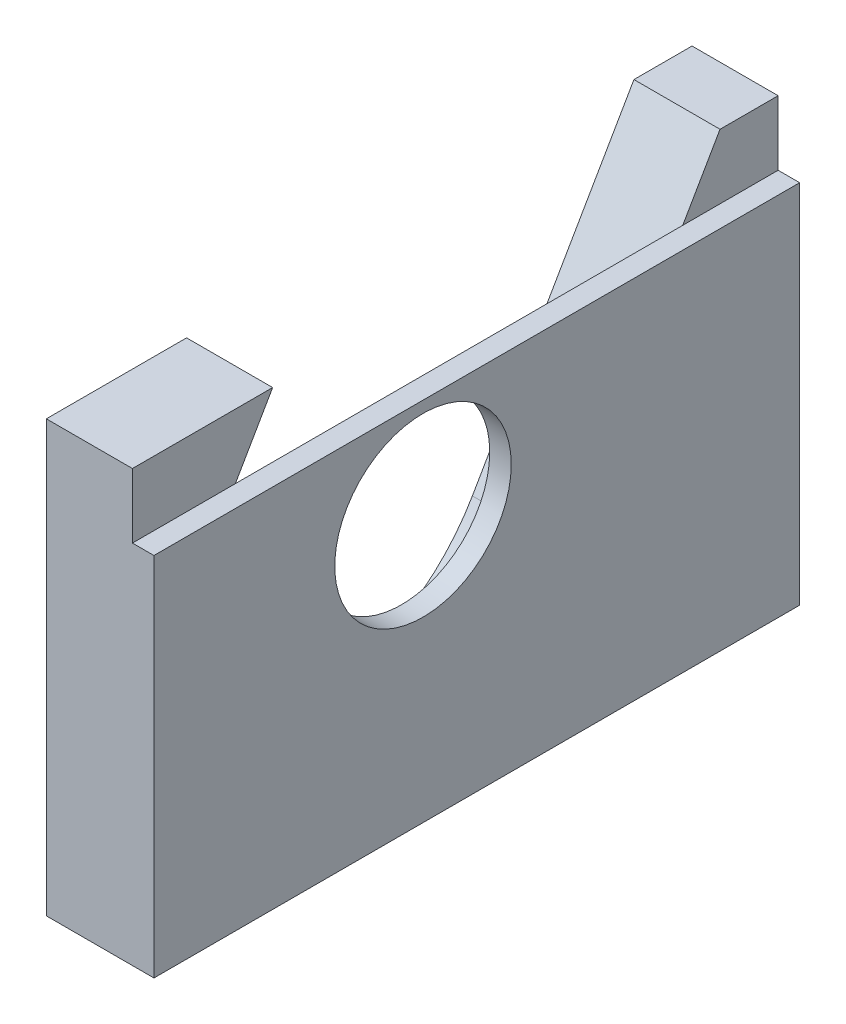
SolidWorks part; units mm, degrees
ref_plane "Front Plane" through (0, 0, 0) normal (0, 0, 1) x (1, 0, 0)
ref_plane "Top Plane" through (0, 0, 0) normal (0, 1, 0) x (1, 0, 0)
ref_plane "Right Plane" through (0, 0, 0) normal (1, 0, 0) x (0, 0, -1)
sketch "Sketch1" plane through (0, 0, 0) normal (1, 0, 0) x (0, 0, -1)
  line L1 (0, 0) -> (30, 0)
  line L2 (0, 0) -> (0, 20)
  line L3 (0, 20) -> (30, 20)
  line L4 (30, 0) -> (30, 20)
  dimension "D1" = 30
  dimension "D2" = 20
extrude "Boss-Extrude1" add sketch "Sketch1" along normal blind 4
sketch "Sketch2" plane through (4, 0, 0) normal (1, 0, 0) x (0, 0, -1)
  line L0 (0, 0) -> (30, 0) construction
  line L1 (0, 20) -> (0, 0) construction
  line L2 (4.2058, 16) -> (19.2058, 41.9808)
  line L3 (19.7942, 7) -> (34.7942, 32.9808)
  line L4 (34.7942, 32.9808) -> (19.2058, 41.9808)
  line L5 (2.2, 0) -> (-2.2, 0) construction
  arc A0 (4.2058, 16) -> (19.7942, 7) centre (12, 11.5) ccw
  point P10 (21.5335, 25.8567)
  dimension "D3" = 18
  dimension "D1" = 11.5
  dimension "D2" = 12
  dimension "D4" = 18
  dimension "D5" = 30
  dimension "60" = 60
extrude "Cut-Extrude1" cut sketch "Sketch2" against normal through all
ref_plane "Plane1" through (0, -2.3212, -4.0204) normal (0, -0.5, -0.866) x (-1, 0, 0)
sketch "Sketch3" plane through (4, 0, 0) normal (1, 0, 0) x (0, 0, -1)
  line L0 (30, 0) -> (30, 20) construction
  line L1 (0, 0) -> (30, 0)
  line L2 (0, 0) -> (0, 17)
  line L3 (0, 17) -> (30, 17)
  line L4 (30, 0) -> (30, 17)
  dimension "D1" = 17
extrude "Boss-Extrude2" add sketch "Sketch3" along normal blind 1
sketch "Sketch4" plane through (5, 0, 0) normal (1, 0, 0) x (0, 0, -1)
  line L0 (2.9204, -4.2264) -> (5.1204, -0.4159) construction
  line L1 (18.1678, 22.1829) -> (7.5, 3.7058) construction
  circle A0 centre (12.5, 12.366) radius 4.1
  arc A2 (4.2058, 16) -> (19.7942, 7) centre (12, 11.5) ccw construction
  point P3 (0, 0)
  dimension "D1" = 8.2
  dimension "D2" = 10
extrude "Cut-Extrude2" cut sketch "Sketch4" against normal through all
equation "\"D4@Sketch2\"=\"D3@Sketch2\""
